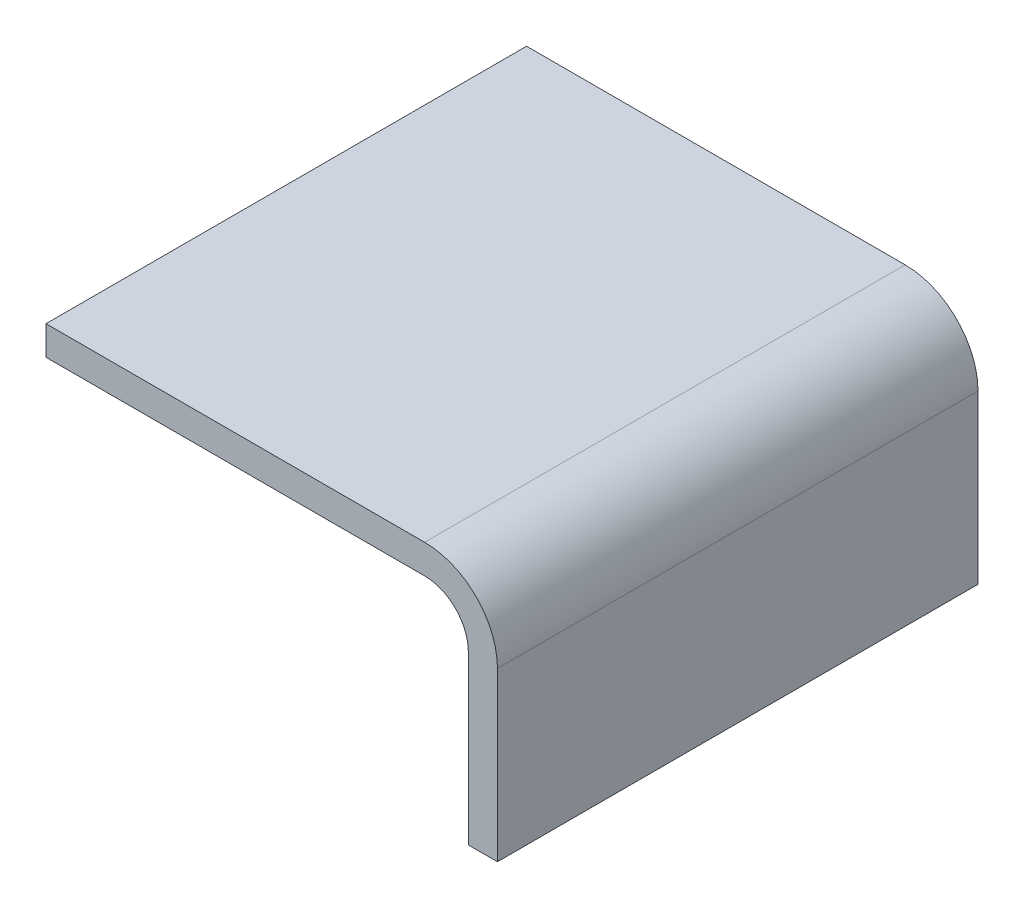
SolidWorks part; units mm, degrees
ref_plane "Front Plane" through (0, 0, 0) normal (0, 0, 1) x (1, 0, 0)
ref_plane "Top Plane" through (0, 0, 0) normal (0, 1, 0) x (1, 0, 0)
ref_plane "Right Plane" through (0, 0, 0) normal (1, 0, 0) x (0, 0, -1)
sketch "Sketch1" plane through (0, 0, 0) normal (0, 0, 1) x (1, 0, 0)
  line L0 (0, 29) -> (52, 29)
  line L3 (0, 33) -> (52, 33)
  line L4 (62, 0) -> (62, 23)
  line L5 (58, 0) -> (58, 23)
  line L6 (62, 0) -> (58, 0)
  line L7 (0, 33) -> (0, 29)
  arc A0 (52, 33) -> (62, 23) centre (52, 23) cw
  arc A1 (52, 29) -> (58, 23) centre (52, 23) cw
  dimension "D3" = 10
  dimension "D4" = 4
extrude "Boss-Extrude1" add sketch "Sketch1" along normal blind 66
